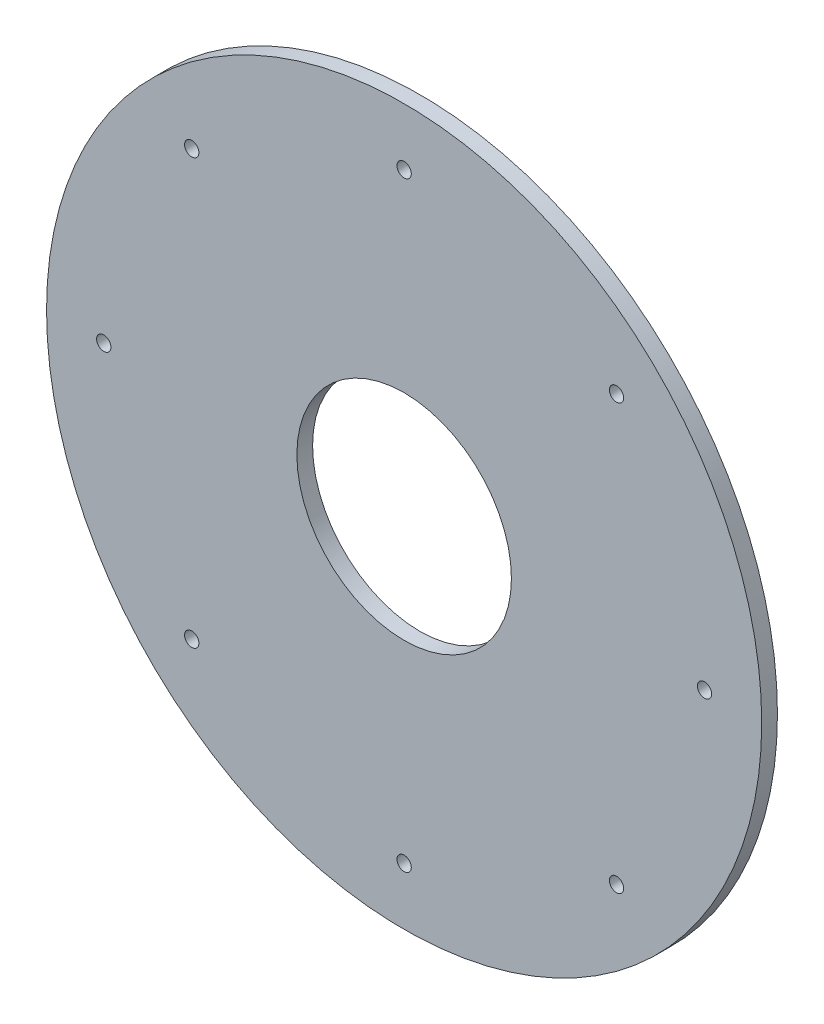
SolidWorks part; units mm, degrees
material "Epoxy, Unfilled"
ref_plane "Ön Düzlem" through (0, 0, 0) normal (0, 0, 1) x (1, 0, 0)
ref_plane "Üst Düzlem" through (0, 0, 0) normal (0, 1, 0) x (1, 0, 0)
ref_plane "Sağ Düzlem" through (0, 0, 0) normal (1, 0, 0) x (0, 0, -1)
sketch "Sketch2" plane through (0, 0, 0) normal (0, 0, 1) x (1, 0, 0)
  circle A0 centre (0, 0) radius 250
  circle A1 centre (0, 0) radius 75
  dimension "D1" = 500
  dimension "D2" = 150
extrude "Boss-Extrude1" add sketch "Sketch2" along normal blind 11
sketch "Sketch3" plane through (0, 0, 11) normal (0, 0, 1) x (1, 0, 0)
  circle A0 centre (0, 0) radius 210 construction
  circle A1 centre (0, 210) radius 5
  circle A2 centre (148.4924, 148.4924) radius 5
  circle A3 centre (210, 0) radius 5
  circle A4 centre (148.4924, -148.4924) radius 5
  circle A5 centre (0, -210) radius 5
  circle A6 centre (-148.4924, -148.4924) radius 5
  circle A7 centre (-210, 0) radius 5
  circle A8 centre (-148.4924, 148.4924) radius 5
  point P21 (0, 0)
  dimension "D1" = 420
  dimension "D2" = 10
  dimension "D3" = 8
extrude "Cut-Extrude1" cut sketch "Sketch3" against normal through all
